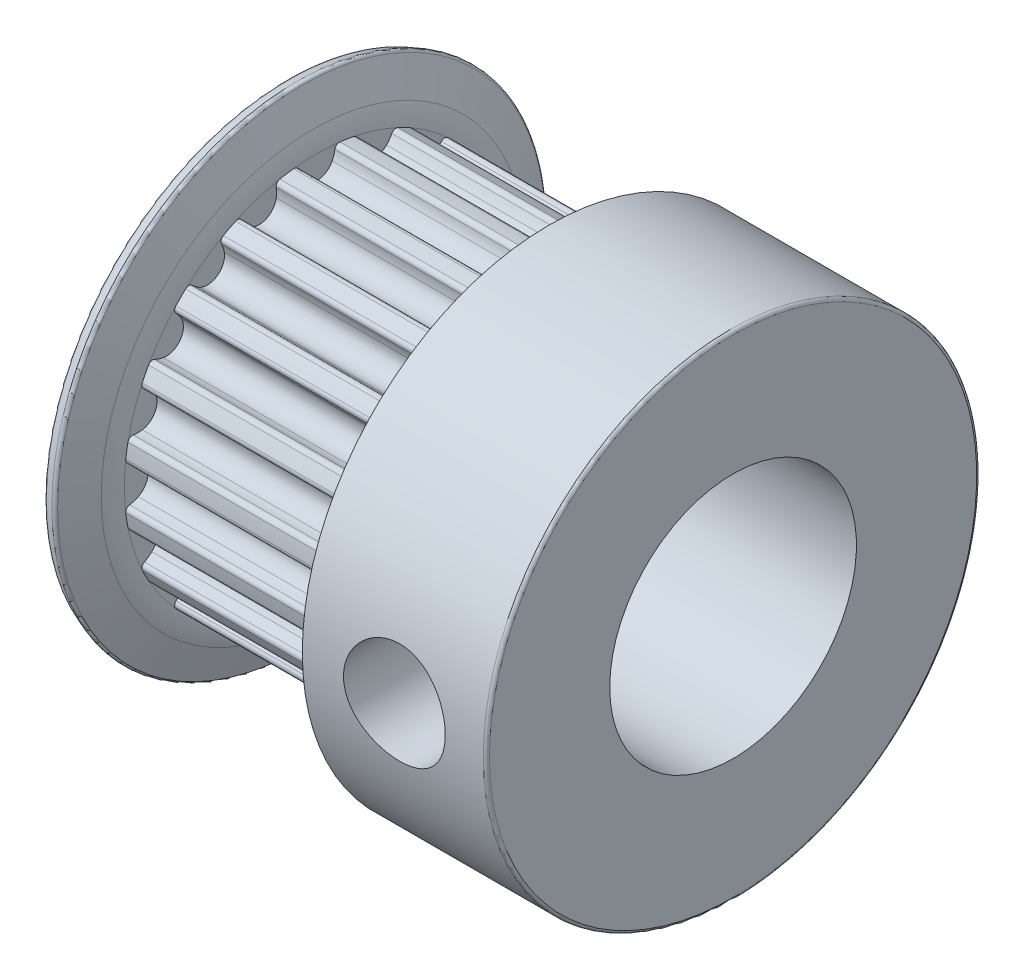
SolidWorks part; units mm, degrees
ref_plane "Front" through (0, 0, 0) normal (0, 0, 1) x (1, 0, 0)
ref_plane "Top" through (0, 0, 0) normal (0, 1, 0) x (1, 0, 0)
ref_plane "Right" through (0, 0, 0) normal (1, 0, 0) x (0, 0, -1)
sketch "Sketch1" plane through (0, 0, 0) normal (1, 0, 0) x (0, 0, -1)
  circle A0 centre (0, 0) radius 4
  circle A1 centre (0, 0) radius 6.2392
  dimension "D1" = 8
  dimension "D2" = 12.4784
extrude "Boss-Extrude1" add sketch "Sketch1" along normal mid plane 7
sketch "Sketch2" plane through (0, 0, 0) normal (1, 0, 0) x (0, 0, -1)
  line L0 (0, 0) -> (0, 6.2392) construction
  circle A0 centre (0, 0) radius 6.2392 construction
  arc A1 (0.7537, 6.1935) -> (-0.7537, 6.1935) centre (0, 0) ccw
  arc A2 (-0.7537, 6.1935) -> (-0.5874, 6.0683) centre (-0.7355, 6.0446) cw
  arc A3 (-0.5874, 6.0683) -> (-0.4989, 5.7882) centre (0.4, 6.2264) ccw
  arc A4 (-0.4989, 5.7882) -> (0.4989, 5.7882) centre (0, 6.0314) ccw
  arc A5 (0.7537, 6.1935) -> (0.5874, 6.0683) centre (0.7355, 6.0446) ccw
  arc A6 (0.5874, 6.0683) -> (0.4989, 5.7882) centre (-0.4, 6.2264) cw
  dimension "D1" = 0.15
  dimension "D2" = 1
  dimension "D3" = 0.555
  dimension "D4" = 0.4
extrude "Cut-Extrude1" cut sketch "Sketch2" against normal mid plane 7
pattern_circular "CirPattern1" count 20 over 360 about axis through (0, 0, 0) along (1, 0, 0) of "Cut-Extrude1"
sketch "Sketch3" plane through (0, 0, 0) normal (0, 0, 1) x (1, 0, 0)
  line L0 (0, 6.2392) -> (0, 0) construction
  line L1 (0, 0) -> (5.1043, 0) construction
  line L2 (-3.5, 4) -> (-3.5, 6.2392)
  line L3 (-3.614, 6.8748) -> (-4.0312, 8)
  line L4 (-4.0312, 8) -> (-4.5, 7.8262)
  line L5 (-4.5, 7.8262) -> (-4.0829, 6.701)
  line L7 (-4, 6.2392) -> (-4, 5)
  line L8 (-4, 5) -> (-4.25, 5)
  line L9 (-4.25, 5) -> (-4.25, 4.5)
  line L10 (-4.25, 4.5) -> (-4.5, 4.5)
  line L11 (-4.5, 4.5) -> (-4.5, 4)
  line L12 (-4.5, 4) -> (-3.5, 4)
  line L16 (4.5, 4.5) -> (4.5, 4)
  line L17 (4.25, 4.5) -> (4.5, 4.5)
  line L18 (4.25, 5) -> (4.25, 4.5)
  line L19 (4, 5) -> (4.25, 5)
  line L20 (4, 6.2392) -> (4, 5)
  line L21 (4.5, 7.8262) -> (4.0829, 6.701)
  line L22 (4.0312, 8) -> (4.5, 7.8262)
  line L23 (3.614, 6.8748) -> (4.0312, 8)
  line L24 (3.5, 4) -> (3.5, 6.2392)
  line L25 (4.5, 4) -> (3.5, 4)
  arc A0 (-3.5, 6.2392) -> (-3.614, 6.8748) centre (-5.3285, 6.2392) ccw
  arc A1 (-4.0829, 6.701) -> (-4, 6.2392) centre (-5.3285, 6.2392) cw
  arc A2 (4.0829, 6.701) -> (4, 6.2392) centre (5.3285, 6.2392) ccw
  arc A3 (3.5, 6.2392) -> (3.614, 6.8748) centre (5.3285, 6.2392) cw
  dimension "D1" = 9
  dimension "D2" = 16
  dimension "D3" = 0.5
  dimension "D4" = 1.2
  dimension "D5" = 1
  dimension "D6" = 10
revolve "Revolve1" add sketch "Sketch3" angle 360 about L1
sketch "Sketch4" plane through (0, 0, 0) normal (0, 0, 1) x (1, 0, 0)
  line L0 (0, 7.2927) -> (0, 0) construction
  line L1 (0, 0) -> (12.9063, 0) construction
  line L2 (4.0312, 8) -> (4.0312, 0) construction
  line L4 (0, 0) -> (5.1043, 0) construction
  line L5 (4.0312, 8) -> (10, 8)
  line L6 (10, 8) -> (10, 4)
  line L7 (10, 4) -> (3.8216, 4)
  line L8 (3.8216, 4) -> (4.0312, 8)
  line L9 (4.5, 4) -> (3.5, 4) construction
  line L10 (-4.5, 4.5) -> (-4.5, 4) construction
  dimension "D1" = 16
  dimension "D2" = 14.5
  dimension "D3" = 93
revolve "Revolve2" add sketch "Sketch4" angle 360 about L1
fillet "Fillet1" radius 0.1 6 edges at (-4, 0, 5) (-4.25, 0, 5) (-4.25, 0, 4.5) (10, 0, 8) (-4.0312, 0, 8) (-4.5, 0, 7.8262)
sketch "Sketch5" plane through (0, 0, 0) normal (0, 0, 1) x (1, 0, 0)
  line L0 (4.0312, 0) -> (10, 0) construction
  line L1 (4.0312, 8) -> (4.0312, 0) construction
  line L2 (10, 8) -> (10, 4) construction
hole_wizard "M4 Tapped Hole1" positions "Sketch7" profile "Sketch6" tap size "M4" standard "ISO"
sketch "Sketch7" plane through (0, 0, 0) normal (0, 0, 1) x (1, 0, 0)
  line L0 (4.0312, 0) -> (10, 0) construction
  point P0 (7.0156, 0)
sketch "Sketch6" plane through (7.0156, 0, 0) normal (1, 0, 0) x (0, 1, 0)
  line L0 (0, 0) -> (0, 8)
  line L1 (0, 8) -> (1.65, 8)
  line L2 (1.65, 8) -> (1.65, 0)
  line L5 (1.65, 0) -> (0, 0)
  line L11 (0, -6.35) -> (0, 107.95) construction
  dimension "Thru Tap Drill Dia." = 3.3
  dimension "Thru Tap Drill Depth" = 8
cosmetic thread "Hole Thread1" parameters "D2"=4
equation "\"Pitch\"= 2"
equation "\"Outside Fillet\"= .15"
equation "\"Side Radius\"= 1"
equation "\"Bottom Radius\"= .555"
equation "\"Tooth height\"= .75"
equation "\"Teeth_Count\"=20"
equation "\"Side radius offset\"= .4"
equation "\"Effective radius offset\"= 0.254"
equation "\"Belt width\"= 6"
equation "\"Pulley extra width\"= 1"
equation "\"Rim_Diameter\"=16"
equation "\"Rim_Width\"= 1"
equation "\"Pulley_Width\"= \"Belt width\" + \"Pulley extra width\" + 2 * \"Rim_Width\""
equation "\"Overall Width\"=14.5"
equation "\"Fastening Diameter\"=16"
equation "\"D2@Sketch1\"=\"Pitch\"*\"Teeth_Count\"/pi - \"Effective radius offset\""
equation "\"D1@Boss-Extrude1\"=\"Belt width\"+\"Pulley extra width\""
equation "\"D1@Sketch2\"=\"Outside Fillet\""
equation "\"D2@Sketch2\"=\"Side Radius\""
equation "\"D3@Sketch2\"=\"Bottom Radius\""
equation "\"D4@Sketch2\"=\"Side radius offset\""
equation "\"D1@Cut-Extrude1\"=\"Belt width\"+\"Pulley extra width\""
equation "\"D1@CirPattern1\"=\"Teeth_Count\""
equation "\"D2@Sketch3\"=\"Rim_Diameter\""
equation "\"D1@Sketch4\"=\"Fastening Diameter\""
equation "\"D2@Sketch4\"=\"Overall Width\""
